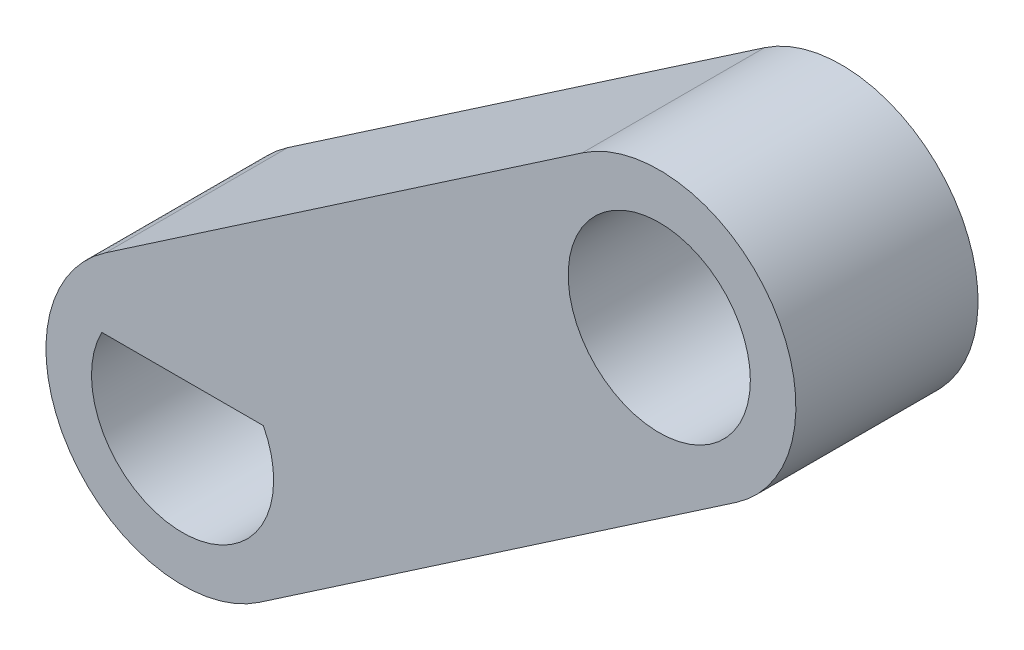
SolidWorks part; units mm, degrees
ref_plane "前视基准面" through (0, 0, 0) normal (0, 0, 1) x (1, 0, 0)
ref_plane "上视基准面" through (0, 0, 0) normal (0, 1, 0) x (1, 0, 0)
ref_plane "右视基准面" through (0, 0, 0) normal (1, 0, 0) x (0, 0, -1)
other "Configuration Table"
sketch "草图1" plane through (0, 0, -35.9137) normal (0, 0, 1) x (1, 0, 0)
  line L0 (-83.5922, 661.1951) -> (-31.2515, 696.8652) construction
  line L1 (-92.0396, 673.5904) -> (-39.6988, 709.2604)
  line L2 (-75.1449, 648.7999) -> (-22.8042, 684.4699)
  line L3 (-74.7224, 665.8131) -> (-92.4621, 665.8131)
  arc A0 (-92.0396, 673.5904) -> (-75.1449, 648.7999) centre (-83.5922, 661.1951) ccw
  arc A1 (-22.8042, 684.4699) -> (-39.6988, 709.2604) centre (-31.2515, 696.8652) ccw
  circle A2 centre (-31.2515, 696.8652) radius 10
  arc A3 (-92.4621, 665.8131) -> (-74.7224, 665.8131) centre (-83.5922, 661.1951) ccw
  point P4 (-57.4219, 679.0302)
  point P13 (-31.2515, 696.8652)
  dimension "D1" = 15
  dimension "D2" = 20
extrude "凸台-拉伸1" add sketch "草图1" along normal blind 20
